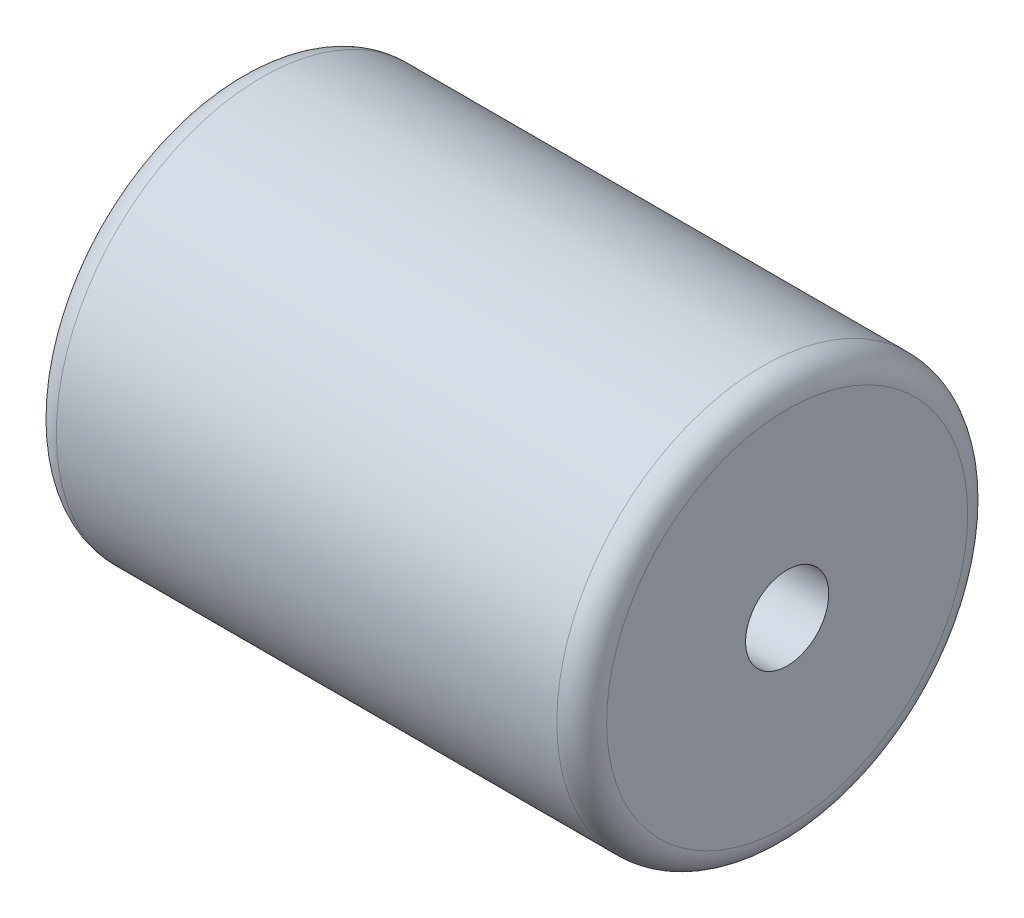
SolidWorks part; units mm, degrees
ref_plane "Front Plane" through (0, 0, 0) normal (0, 0, 1) x (1, 0, 0)
ref_plane "Top Plane" through (0, 0, 0) normal (0, 1, 0) x (1, 0, 0)
ref_plane "Right Plane" through (0, 0, 0) normal (1, 0, 0) x (0, 0, -1)
sketch "Sketch1" plane through (0, 0, 0) normal (1, 0, 0) x (0, 0, -1)
  circle A0 centre (0, 0) radius 5.2387
  circle A1 centre (0, 0) radius 1.0605
  dimension "D1" = 10.4775
  dimension "D2" = 2.1209
extrude "Boss-Extrude1" add sketch "Sketch1" along normal blind 14.0335
fillet "Fillet1" radius 0.635 2 edges at (0, 0, -5.2387) (14.0335, 0, -5.2387)
